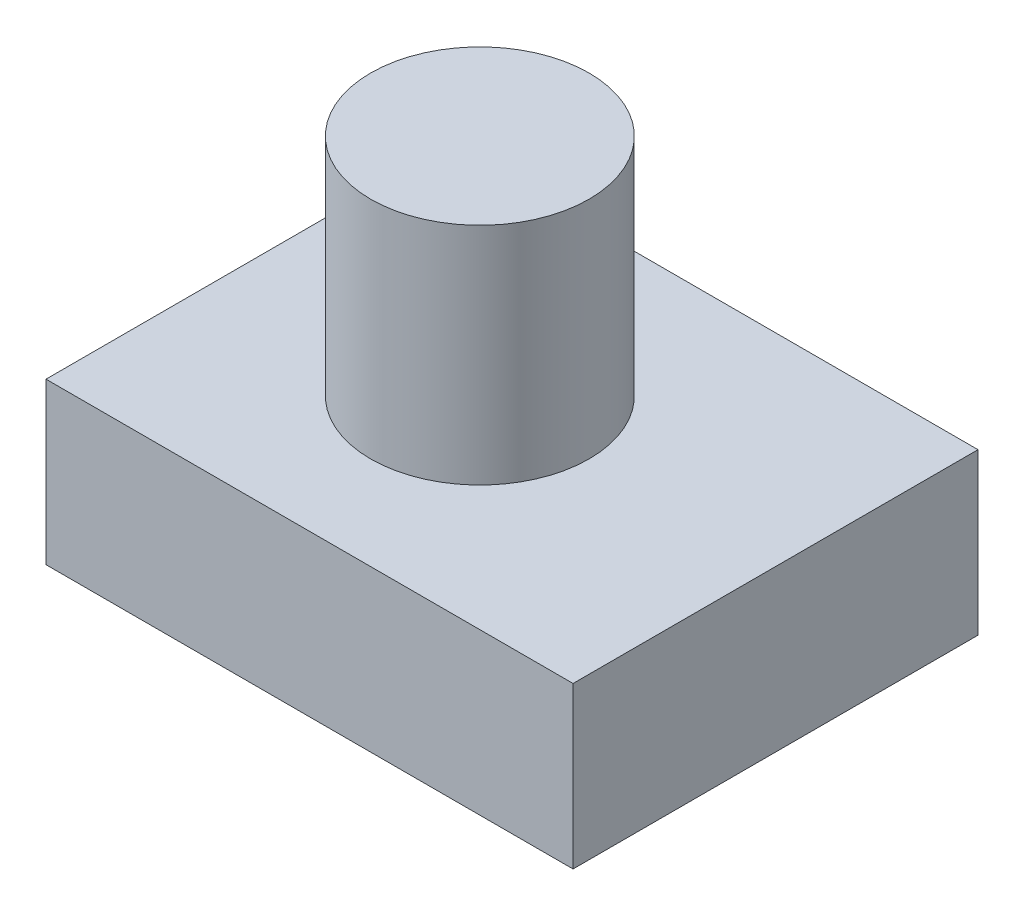
SolidWorks part; units mm, degrees
ref_plane "Front Plane" through (0, 0, 0) normal (0, 0, 1) x (1, 0, 0)
ref_plane "Top Plane" through (0, 0, 0) normal (0, 1, 0) x (1, 0, 0)
ref_plane "Right Plane" through (0, 0, 0) normal (1, 0, 0) x (0, 0, -1)
sketch "Sketch1" plane through (0, 0, 0) normal (0, 1, 0) x (1, 0, 0)
  line L1 (-38.0714, 18.2121) -> (43.9286, 18.2121)
  line L2 (-38.0714, 18.2121) -> (-38.0714, -44.7879)
  line L3 (-38.0714, -44.7879) -> (43.9286, -44.7879)
  line L4 (43.9286, 18.2121) -> (43.9286, -44.7879)
  dimension "D1" = 82
  dimension "D2" = 63
extrude "Boss-Extrude1" add sketch "Sketch1" along normal blind 25
sketch "Sketch2" plane through (0, 25, 0) normal (0, 1, 0) x (1, 0, 0)
  line L0 (43.9286, -44.7879) -> (43.9286, 18.2121) construction
  line L1 (43.9286, 18.2121) -> (-38.0714, 18.2121) construction
  circle A0 centre (-2.0714, -13.2879) radius 17
  dimension "D1" = 34
  dimension "D2" = 46
  dimension "D3" = 31.5
extrude "Boss-Extrude2" add sketch "Sketch2" along normal blind 35
scale "Scale1" scale about centroid uniform scaling yes scale factor 0.1
